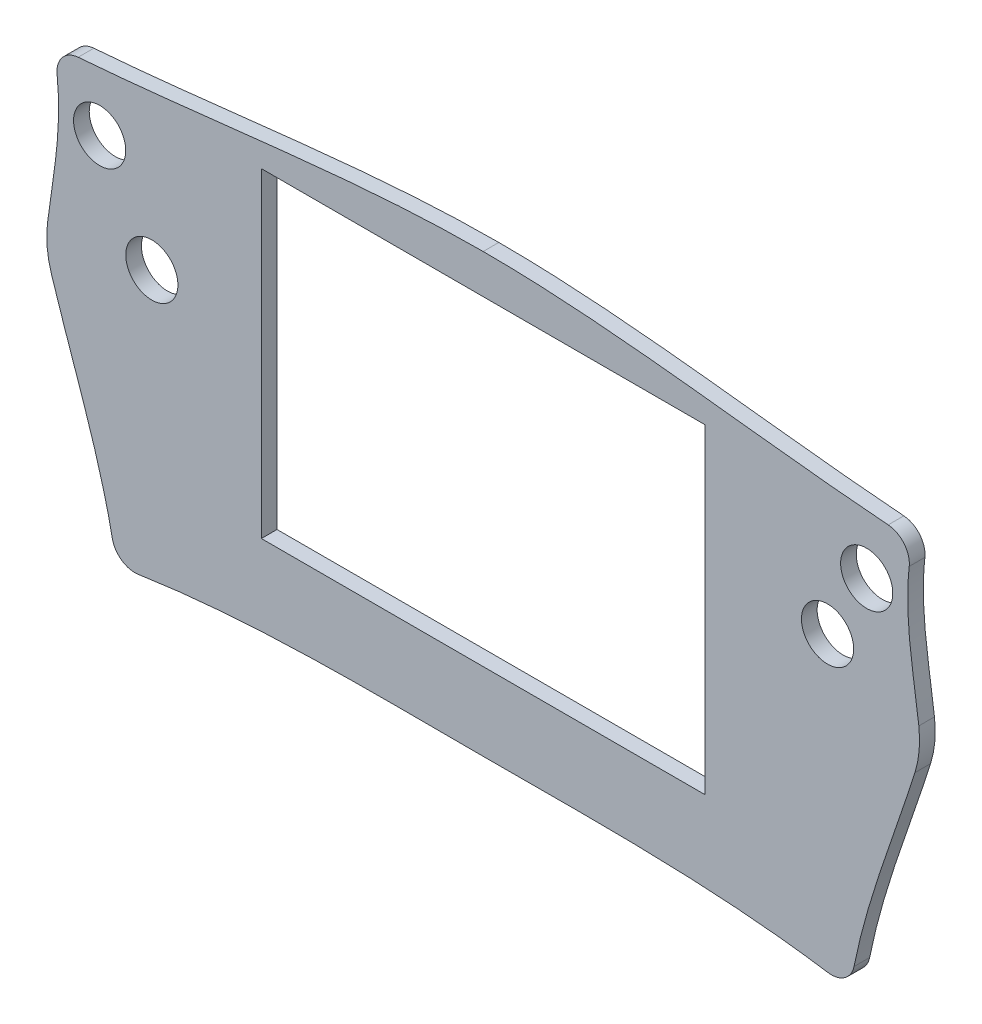
SolidWorks part; units mm, degrees
ref_plane "Front Plane" through (0, 0, 0) normal (0, 0, 1) x (1, 0, 0)
ref_plane "Top Plane" through (0, 0, 0) normal (0, 1, 0) x (1, 0, 0)
ref_plane "Right Plane" through (0, 0, 0) normal (1, 0, 0) x (0, 0, -1)
sketch "Sketch1" plane through (0, 0, 0) normal (0, 0, 1) x (1, 0, 0)
  line L0 (-93.3384, 84.9651) -> (-80.6384, 62.968) construction
  line L1 (-53.975, 97.6651) -> (53.975, 97.6651)
  line L2 (-53.975, 97.6651) -> (-53.975, 19.6871)
  line L3 (-53.975, 19.6871) -> (53.975, 19.6871)
  line L4 (53.975, 97.6651) -> (53.975, 19.6871)
  line L5 (83.8447, 68.4673) -> (93.3697, 84.9651) construction
  line L6 (-1053.4632, 91.3151) -> (48946.5368, 91.3151) construction
  line L7 (-93.3384, 84.9651) -> (-98.1384, 93.2788) construction
  line L8 (93.3697, 84.9651) -> (98.1696, 93.2788) construction
  arc A0 (-90.9952, 1.4308) -> (-83.8129, -3.6021) centre (-84.7684, 2.6757) ccw construction
  arc A1 (91.0264, 1.4308) -> (83.8442, -3.6021) centre (84.7996, 2.6757) cw construction
  arc A2 (104.4808, 92.5779) -> (98.6567, 99.6101) centre (98.1696, 93.2788) ccw construction
  arc A3 (-104.4496, 92.5779) -> (-98.6254, 99.6101) centre (-98.1384, 93.2788) cw construction
  arc A4 (105.8354, 49.6367) -> (106.8178, 60.2997) centre (81.602, 57.2461) ccw construction
  arc A5 (-105.8042, 49.6367) -> (-106.7866, 60.2997) centre (-81.5708, 57.2461) cw construction
  arc A6 (-90.2479, 1.5802) -> (-83.9276, -2.8487) centre (-84.7684, 2.6757) ccw
  arc A7 (90.2792, 1.5802) -> (83.9588, -2.8487) centre (84.7996, 2.6757) cw
  arc A8 (105.1084, 49.865) -> (106.0613, 60.2081) centre (81.602, 57.2461) ccw
  arc A9 (103.7234, 92.662) -> (98.5982, 98.8503) centre (98.1696, 93.2788) ccw
  arc A10 (-103.6922, 92.662) -> (-98.567, 98.8503) centre (-98.1384, 93.2788) cw
  arc A11 (-105.0772, 49.865) -> (-106.0301, 60.2081) centre (-81.5708, 57.2461) cw
  circle A12 centre (-93.3384, 84.9651) radius 6.35
  circle A13 centre (93.3697, 84.9651) radius 6.35
  circle A14 centre (-80.6384, 62.968) radius 6.35
  circle A15 centre (83.8447, 68.4673) radius 6.35
  spline S0 degree 3 poles (0, 0) (5.1735, 0.0127) (10.3471, 0.026) (15.5307, 0.04) (15.539, 0.04) (18.6201, 0.0483) (21.4623, 0.0491) (25.3867, 0.0393) (27.5771, 0.0304) (29.8788, 0.0136) (30.9717, 0.0034) (31.2425, 0.0008) (31.2454, 0.0007) (34.1264, -0.0278) (38.2682, -0.0931) (43.44, -0.2256) (45.9085, -0.3068) (47.1196, -0.3514) (47.1275, -0.3517) (49.962, -0.4562) (54.7735, -0.6793) (60.0041, -1.0158) (62.5414, -1.2072) (63.1737, -1.2567) (63.1822, -1.2573) (68.9953, -1.7129) (75.9402, -2.4511) (82.5675, -3.4078) (83.8442, -3.6021) knots 0 0 0 0 0.124756 0.124756 0.125 0.125 0.1875 0.1875 0.21875 0.242187 0.249878 0.249878 0.25 0.25 0.3125 0.34375 0.374756 0.374756 0.375 0.375 0.4375 0.484375 0.499756 0.499756 0.5 0.5 0.625 0.655173 0.655173 0.655173 0.655173 construction
  spline S1 degree 3 poles (-83.8129, -3.6021) (-82.5389, -3.4082) (-75.9152, -2.4519) (-68.9739, -1.7139) (-63.1502, -1.2573) (-63.132, -1.2559) (-60.6031, -1.0581) (-55.4198, -0.7108) (-49.9434, -0.4568) (-47.0982, -0.3518) (-47.0806, -0.3511) (-45.8695, -0.3066) (-43.4112, -0.2257) (-38.2513, -0.0934) (-34.1104, -0.028) (-31.2131, 0.0007) (-31.1984, 0.0009) (-30.1448, 0.0112) (-27.9298, 0.0283) (-25.463, 0.0383) (-21.5413, 0.0482) (-18.6702, 0.0477) (-15.5169, 0.04) (-15.4974, 0.0399) (-12.9014, 0.0336) (-10.3257, 0.0257) (-7.4256, 0.0151) (-7.1042, 0.014) (-4.5208, 0.0055) (-2.2604, 0.0012) (0, 0) knots 0.344884 0.344884 0.344884 0.344884 0.375 0.5 0.5 0.500488 0.500488 0.5625 0.625 0.625 0.625488 0.625488 0.65625 0.6875 0.75 0.75 0.750488 0.750488 0.78125 0.8125 0.8125 0.875 0.875 0.875488 0.875488 0.9375 0.9375 0.945312 0.945312 1 1 1 1 construction
  spline S2 degree 3 poles (91.0264, 1.4308) (93.358, 13.0932) (97.1393, 24.0412) (102.5678, 39.7371) (104.2841, 44.6964) (105.8354, 49.6367) knots -0.293558 -0.293558 -0.293558 -0.293558 0.5 0.5 0.87305 0.87305 0.87305 0.87305 construction
  spline S3 degree 3 poles (106.8178, 60.2997) (106.791, 60.5208) (106.7637, 60.7423) (106.4675, 63.1015) (105.8334, 67.4586) (105.1805, 71.989) (104.1938, 80.083) (103.7679, 86.159) (104.4808, 92.5779) knots 0.224038 0.224038 0.224038 0.224038 0.25 0.25 0.5 0.75 0.75 1.37521 1.37521 1.37521 1.37521 construction
  spline S4 degree 3 poles (98.6567, 99.6101) (97.303, 99.7142) (95.9504, 99.8237) (83.9121, 100.8408) (62.6582, 103.2369) (41.6376, 105.6033) (20.7362, 107.3693) (10.3458, 107.9521) (0.0156, 107.9521) knots 0.218379 0.218379 0.218379 0.218379 0.25 0.25 0.5 0.75 0.75 1 1 1 1 construction
  spline S5 degree 3 poles (0.0156, 107.9521) (-10.3146, 107.9521) (-20.705, 107.3693) (-41.6063, 105.6033) (-62.627, 103.2369) (-83.8808, 100.8408) (-95.9191, 99.8237) (-97.2718, 99.7142) (-98.6254, 99.6101) knots 0 0 0 0 0.25 0.25 0.5 0.75 0.75 0.781621 0.781621 0.781621 0.781621 construction
  spline S6 degree 3 poles (-105.8042, 49.6367) (-104.2529, 44.6964) (-102.5366, 39.7371) (-97.108, 24.0412) (-93.3267, 13.0932) (-90.9952, 1.4308) knots 0.12695 0.12695 0.12695 0.12695 0.5 0.5 1.293558 1.293558 1.293558 1.293558 construction
  spline S7 degree 3 poles (-104.4496, 92.5779) (-103.7367, 86.159) (-104.1626, 80.083) (-105.1492, 71.989) (-105.8022, 67.4586) (-106.4363, 63.1015) (-106.7325, 60.7423) (-106.7598, 60.5208) (-106.7866, 60.2997) knots -0.37521 -0.37521 -0.37521 -0.37521 0.25 0.25 0.5 0.75 0.75 0.775962 0.775962 0.775962 0.775962 construction
  spline S8 degree 1 poles (-83.9276, -2.8487) (-0.0007, 0.762) knots 0 0 1 1 construction
  spline S9 degree 1 poles (-0.0007, 0.762) (83.9588, -2.8487) knots 0 0 1 1 construction
  spline S10 degree 1 poles (90.2792, 1.5802) (105.1084, 49.865) knots 0 0 1 1 construction
  spline S11 degree 1 poles (106.0613, 60.2081) (103.7234, 92.662) knots 0 0 1 1 construction
  spline S12 degree 1 poles (98.5982, 98.8503) (0.0156, 107.1901) knots 0 0 1 1 construction
  spline S13 degree 1 poles (0.0156, 107.1901) (-98.567, 98.8503) knots 0 0 1 1 construction
  spline S14 degree 1 poles (-103.6922, 92.662) (-106.0301, 60.2081) knots 0 0 1 1 construction
  spline S15 degree 1 poles (-105.0772, 49.865) (-90.2479, 1.5802) knots 0 0 1 1 construction
  spline S16 degree 3 poles (-83.9276, -2.8487) (-83.0541, -2.7158) (-81.3127, -2.4601) (-78.6543, -2.0975) (-75.9665, -1.7582) (-72.337, -1.3362) (-68.6439, -0.9599) (-65.584, -0.6905) (-64.1668, -0.5737) (-63.5661, -0.5256) (-63.1042, -0.4893) (-62.6999, -0.458) (-61.9625, -0.4018) (-60.9159, -0.3251) (-59.2176, -0.2068) (-57.0682, -0.0687) (-54.4397, 0.082) (-51.767, 0.2174) (-49.4909, 0.318) (-48.009, 0.3766) (-47.3036, 0.4032) (-46.8762, 0.4189) (-46.1962, 0.4433) (-45.1759, 0.478) (-43.5402, 0.5294) (-41.4429, 0.5878) (-38.8565, 0.648) (-36.1958, 0.6983) (-33.9194, 0.7322) (-32.4068, 0.7502) (-31.7062, 0.7578) (-31.4084, 0.7608) (-31.1812, 0.7631) (-31.0214, 0.7646) (-30.7077, 0.7676) (-30.2699, 0.7715) (-29.5464, 0.7775) (-28.6196, 0.7841) (-27.465, 0.791) (-25.8712, 0.7987) (-23.7764, 0.8053) (-21.0954, 0.8088) (-18.7302, 0.8079) (-16.9889, 0.8052) (-16.1182, 0.8034) (-15.5864, 0.8022) (-15.1606, 0.8011) (-14.6294, 0.7998) (-13.7789, 0.7975) (-12.2906, 0.7934) (-10.1656, 0.787) (-7.6097, 0.7776) (-4.2329, 0.7667) (-1.6926, 0.7629) (-0.0007, 0.762) knots 0.344884 0.344884 0.344884 0.344884 0.365356 0.385828 0.4063 0.426772 0.467716 0.488188 0.493306 0.498424 0.500984 0.503543 0.508661 0.518897 0.529133 0.549605 0.570077 0.590549 0.611021 0.621257 0.623816 0.626375 0.631493 0.641729 0.651965 0.672437 0.692909 0.713381 0.733854 0.74409 0.746649 0.749208 0.750487 0.751767 0.754326 0.759444 0.764562 0.774798 0.785034 0.79527 0.815742 0.836214 0.856686 0.866922 0.87204 0.874599 0.877158 0.882276 0.887394 0.89763 0.918102 0.938575 0.959047 0.999991 0.999991 0.999991 0.999991
  spline S17 degree 3 poles (-0.0007, 0.762) (1.6973, 0.7662) (4.2444, 0.7725) (7.6405, 0.7812) (10.1877, 0.7878) (12.3099, 0.7934) (13.7963, 0.7973) (14.6443, 0.7996) (15.1776, 0.801) (15.5967, 0.8022) (16.1183, 0.8035) (16.974, 0.8055) (18.6883, 0.8084) (21.028, 0.8096) (23.6979, 0.8063) (25.7999, 0.7996) (27.4093, 0.7918) (28.5803, 0.7848) (29.5252, 0.778) (30.265, 0.7719) (30.7153, 0.7679) (31.0358, 0.7648) (31.2033, 0.7632) (31.4247, 0.761) (31.7255, 0.7579) (32.4247, 0.7504) (33.9391, 0.7323) (36.2152, 0.6986) (38.8771, 0.6482) (41.4644, 0.5881) (43.5624, 0.5297) (45.1991, 0.4783) (46.219, 0.4436) (46.9009, 0.4192) (47.3259, 0.4035) (48.0323, 0.377) (49.5136, 0.3184) (51.7907, 0.2178) (54.4639, 0.0824) (57.0932, -0.0683) (59.2433, -0.2064) (60.9421, -0.3247) (61.9892, -0.4015) (62.7268, -0.4576) (63.1316, -0.489) (63.5924, -0.5252) (64.1937, -0.5734) (65.6109, -0.6901) (68.6718, -0.9595) (72.3655, -1.3358) (75.9958, -1.758) (78.6842, -2.0973) (81.3433, -2.46) (83.0851, -2.7158) (83.9588, -2.8487) knots 0.000009 0.000009 0.000009 0.000009 0.040957 0.061431 0.081905 0.102378 0.112615 0.117734 0.122852 0.125412 0.127971 0.133089 0.143326 0.1638 0.184274 0.204748 0.214985 0.225222 0.235459 0.240577 0.245696 0.248255 0.249534 0.250814 0.253373 0.255932 0.266169 0.286643 0.307117 0.327591 0.348065 0.358302 0.368539 0.373657 0.376216 0.378776 0.389013 0.409486 0.42996 0.450434 0.470908 0.481145 0.491382 0.4965 0.49906 0.501619 0.506737 0.511856 0.53233 0.573277 0.593751 0.614225 0.634699 0.655173 0.655173 0.655173 0.655173
  spline S18 degree 3 poles (90.2792, 1.5802) (90.7073, 3.7213) (91.6711, 8.0016) (93.9035, 16.3317) (97.1434, 26.4672) (100.5871, 36.3067) (103.2449, 44.085) (104.5003, 47.9284) (105.1084, 49.865) knots -0.293558 -0.293558 -0.293558 -0.293558 -0.147732 -0.001906 0.289746 0.581398 0.727224 0.87305 0.87305 0.87305 0.87305
  spline S19 degree 3 poles (106.0613, 60.2081) (105.9117, 61.4441) (105.584, 63.8876) (104.8451, 68.9626) (103.9069, 75.5268) (103.3306, 82.4483) (103.3452, 87.4908) (103.5043, 90.4232) (103.641, 91.9197) (103.7234, 92.662) knots 0.224038 0.224038 0.224038 0.224038 0.367934 0.511831 0.799624 1.087417 1.231313 1.303262 1.37521 1.37521 1.37521 1.37521
  spline S20 degree 3 poles (98.5982, 98.8503) (94.4161, 99.172) (86.05, 99.9192) (69.4226, 101.6741) (48.7792, 104.0869) (28.3446, 106.0814) (12.109, 107.0125) (4.0527, 107.1901) (0.0156, 107.1901) knots 0.218379 0.218379 0.218379 0.218379 0.316081 0.413784 0.609189 0.804595 0.902297 1 1 1 1
  spline S21 degree 3 poles (0.0156, 107.1901) (-4.0215, 107.1901) (-12.0778, 107.0125) (-28.3134, 106.0814) (-48.7479, 104.0869) (-69.3913, 101.6741) (-86.0187, 99.9192) (-94.3849, 99.172) (-98.567, 98.8503) knots 0 0 0 0 0.097703 0.195405 0.390811 0.586216 0.683919 0.781621 0.781621 0.781621 0.781621
  spline S22 degree 3 poles (-103.6922, 92.662) (-103.6098, 91.9197) (-103.4731, 90.4232) (-103.314, 87.4908) (-103.2994, 82.4483) (-103.8757, 75.5268) (-104.8139, 68.9626) (-105.5527, 63.8876) (-105.8804, 61.4441) (-106.0301, 60.2081) knots -0.37521 -0.37521 -0.37521 -0.37521 -0.303262 -0.231313 -0.087417 0.200376 0.488169 0.632066 0.775962 0.775962 0.775962 0.775962
  spline S23 degree 3 poles (-105.0772, 49.865) (-104.4691, 47.9284) (-103.2137, 44.085) (-100.5558, 36.3067) (-97.1121, 26.4672) (-93.8723, 16.3317) (-91.6399, 8.0016) (-90.676, 3.7213) (-90.2479, 1.5802) knots 0.12695 0.12695 0.12695 0.12695 0.272776 0.418602 0.710254 1.001906 1.147732 1.293558 1.293558 1.293558 1.293558
  dimension "D1" = 6.35
  dimension "D2" = 25.4
  dimension "D9" = 12.7
  dimension "D10" = 12.7
  dimension "D11" = 12.7
  dimension "D12" = 12.7
  dimension "D4" = 107.95
  dimension "D5" = 77.978
  dimension "D6" = 53.975
  dimension "D7" = 9.525
  dimension "D8" = 30
  dimension "D13" = 30
  dimension "D14" = 6.35
  dimension "D15" = 25.4
  dimension "D16" = 25.4
  dimension "D3" = 0.762
extrude "Boss-Extrude1" add sketch "Sketch1" along normal blind 3.81
